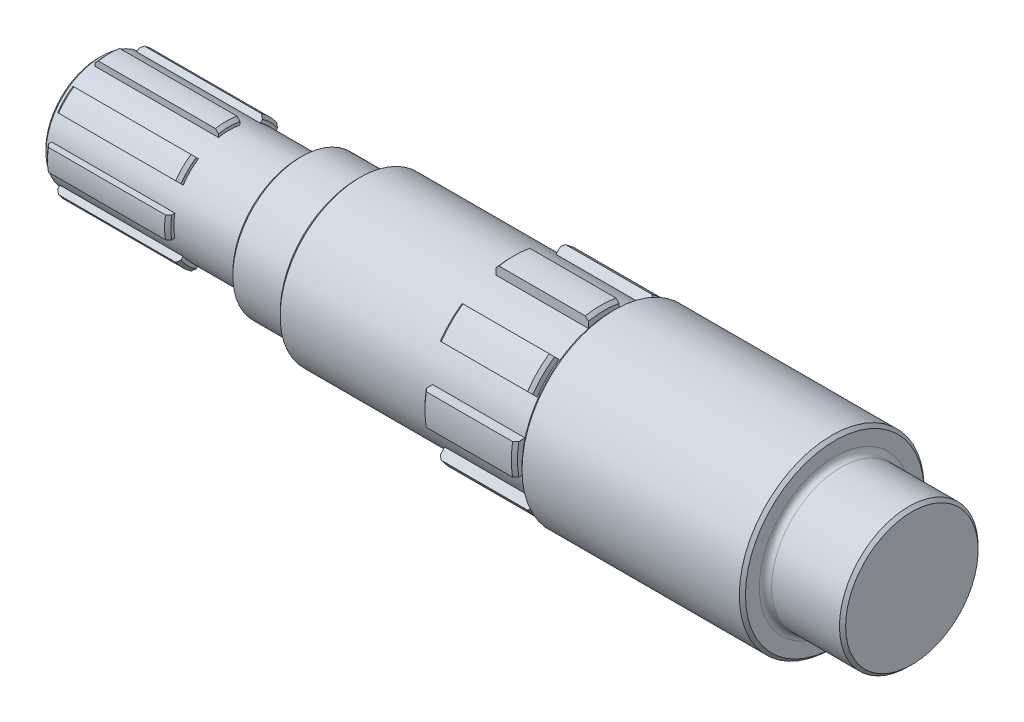
SolidWorks part; units mm, degrees
ref_plane "Front Plane" through (0, 0, 0) normal (0, 0, 1) x (1, 0, 0)
ref_plane "Top Plane" through (0, 0, 0) normal (0, 1, 0) x (1, 0, 0)
ref_plane "Right Plane" through (0, 0, 0) normal (1, 0, 0) x (0, 0, -1)
sketch "Sketch1" plane through (0, 0, 0) normal (0, 0, 1) x (1, 0, 0)
  line L0 (-155.9565, 0) -> (190.3478, 0) construction
  line L1 (-90.9565, 18) -> (-90.9565, 22.3478)
  line L2 (-90.9565, 22.3478) -> (-71.9565, 22.3478)
  line L3 (-71.9565, 22.3478) -> (-71.9565, 26)
  line L4 (-71.9565, 26) -> (-21.9565, 26)
  line L5 (10.5435, 26) -> (10.5435, 30)
  line L6 (10.5435, 30) -> (83.0435, 30)
  line L7 (83.0435, 30) -> (83.0435, 22.5)
  line L8 (83.0435, 22.5) -> (108.0435, 22.5)
  line L9 (108.0435, 22.5) -> (108.0435, 0)
  line L10 (-21.9565, 26) -> (-21.9565, 29)
  line L11 (-21.9565, 29) -> (8.0435, 29)
  line L12 (8.0435, 29) -> (8.0435, 26)
  line L13 (8.0435, 26) -> (10.5435, 26)
  line L14 (-90.9565, 18) -> (-113.4565, 18)
  line L15 (-155.9565, 18) -> (-155.9565, 0)
  line L16 (-155.9565, 0) -> (108.0435, 0)
  line L17 (-153.4565, 18) -> (-153.4565, 20)
  line L18 (-153.4565, 20) -> (-113.4565, 20)
  line L19 (-113.4565, 20) -> (-113.4565, 18)
  line L20 (-153.4565, 18) -> (-155.9565, 18)
  point P3 (-133.4565, 18)
  point P11 (-6.9565, 26)
  point P19 (-155.9565, 75.4675)
  dimension "D2" = 19
  dimension "D3" = 82.5
  dimension "D4" = 72.5
  dimension "D5" = 25
  dimension "D6" = 52
  dimension "D7" = 60
  dimension "D8" = 45
  dimension "D9" = 17.5
  dimension "D10" = 15
  dimension "D11" = 30
  dimension "D12" = 58
  dimension "D13" = 65
  dimension "D14" = 36
  dimension "D15" = 2.5
  dimension "D16" = 20
  dimension "D17" = 40
  dimension "D18" = 20
revolve "Revolve1" add sketch "Sketch1" angle 360 about L0
chamfer "Chamfer1" distance 1 angle 45 10 edges at (108.0435, 0, 22.5) (83.0435, 0, 30) (10.5435, 0, 30) (8.0435, 0, 29) (-21.9565, 0, 29) (-71.9565, 0, 26) (-90.9565, 0, 22.3478) (-113.4565, 0, 20) (-153.4565, 0, 20) (-155.9565, 0, 18)
sketch "Sketch2" plane through (-153.4565, 0, 0) normal (-1, 0, 0) x (0, 0, 1)
  line L0 (0, 0) -> (0, 34.2808) construction
  line L1 (-3.5, 19.6914) -> (-3.5, 17.6564)
  line L2 (3.5, 19.6914) -> (3.5, 17.6564)
  line L3 (16.3988, 11.449) -> (14.9599, 10.0101)
  line L4 (11.449, 16.3988) -> (10.0101, 14.9599)
  line L5 (19.6914, -3.5) -> (17.6564, -3.5)
  line L6 (19.6914, 3.5) -> (17.6564, 3.5)
  line L7 (11.449, -16.3988) -> (10.0101, -14.9599)
  line L8 (16.3988, -11.449) -> (14.9599, -10.0101)
  line L9 (-3.5, -19.6914) -> (-3.5, -17.6564)
  line L10 (3.5, -19.6914) -> (3.5, -17.6564)
  line L11 (-16.3988, -11.449) -> (-14.9599, -10.0101)
  line L12 (-11.449, -16.3988) -> (-10.0101, -14.9599)
  line L13 (-19.6914, 3.5) -> (-17.6564, 3.5)
  line L14 (-19.6914, -3.5) -> (-17.6564, -3.5)
  line L15 (-11.449, 16.3988) -> (-10.0101, 14.9599)
  line L16 (-16.3988, 11.449) -> (-14.9599, 10.0101)
  circle A0 centre (0, 0) radius 20 construction
  circle A1 centre (0, 0) radius 18 construction
  arc A2 (-3.5, 19.6914) -> (-11.449, 16.3988) centre (0, 0) ccw
  arc A3 (-3.5, 17.6564) -> (-10.0101, 14.9599) centre (0, 0) ccw
  arc A4 (11.449, 16.3988) -> (3.5, 19.6914) centre (0, 0) ccw
  arc A5 (10.0101, 14.9599) -> (3.5, 17.6564) centre (0, 0) ccw
  arc A6 (-16.3988, 11.449) -> (-19.6914, 3.5) centre (0, 0) ccw
  arc A7 (-14.9599, 10.0101) -> (-17.6564, 3.5) centre (0, 0) ccw
  arc A8 (-19.6914, -3.5) -> (-16.3988, -11.449) centre (0, 0) ccw
  arc A9 (-17.6564, -3.5) -> (-14.9599, -10.0101) centre (0, 0) ccw
  arc A10 (-11.449, -16.3988) -> (-3.5, -19.6914) centre (0, 0) ccw
  arc A11 (-10.0101, -14.9599) -> (-3.5, -17.6564) centre (0, 0) ccw
  arc A12 (3.5, -19.6914) -> (11.449, -16.3988) centre (0, 0) ccw
  arc A13 (3.5, -17.6564) -> (10.0101, -14.9599) centre (0, 0) ccw
  arc A14 (16.3988, -11.449) -> (19.6914, -3.5) centre (0, 0) ccw
  arc A15 (14.9599, -10.0101) -> (17.6564, -3.5) centre (0, 0) ccw
  arc A16 (19.6914, 3.5) -> (16.3988, 11.449) centre (0, 0) ccw
  arc A17 (17.6564, 3.5) -> (14.9599, 10.0101) centre (0, 0) ccw
  point P41 (0, 0)
  dimension "D1" = 3.5
  dimension "D2" = 8
extrude "Cut-Extrude1" cut sketch "Sketch2" against normal up to surface (40 mm away) up to face at (-113.4565, 0, 19)
sketch "Sketch3" plane through (-21.9565, 0, 0) normal (-1, 0, 0) x (0, 0, 1)
  line L0 (0, 0) -> (0, 40.4461) construction
  line L1 (-5, 28.5657) -> (-5, 25.5147)
  line L2 (5, 28.5657) -> (5, 25.5147)
  line L3 (16.6635, 23.7345) -> (14.5061, 21.5772)
  line L4 (23.7345, 16.6635) -> (21.5772, 14.5061)
  line L5 (28.5657, 5) -> (25.5147, 5)
  line L6 (28.5657, -5) -> (25.5147, -5)
  line L7 (23.7345, -16.6635) -> (21.5772, -14.5061)
  line L8 (16.6635, -23.7345) -> (14.5061, -21.5772)
  line L9 (5, -28.5657) -> (5, -25.5147)
  line L10 (-5, -28.5657) -> (-5, -25.5147)
  line L11 (-16.6635, -23.7345) -> (-14.5061, -21.5772)
  line L12 (-23.7345, -16.6635) -> (-21.5772, -14.5061)
  line L13 (-28.5657, -5) -> (-25.5147, -5)
  line L14 (-28.5657, 5) -> (-25.5147, 5)
  line L15 (-23.7345, 16.6635) -> (-21.5772, 14.5061)
  line L16 (-16.6635, 23.7345) -> (-14.5061, 21.5772)
  circle A0 centre (0, 0) radius 26 construction
  circle A1 centre (0, 0) radius 29 construction
  arc A2 (-5, 25.5147) -> (-14.5061, 21.5772) centre (0, 0) ccw
  arc A3 (-5, 28.5657) -> (-16.6635, 23.7345) centre (0, 0) ccw
  arc A4 (16.6635, 23.7345) -> (5, 28.5657) centre (0, 0) ccw
  arc A5 (14.5061, 21.5772) -> (5, 25.5147) centre (0, 0) ccw
  arc A6 (28.5657, 5) -> (23.7345, 16.6635) centre (0, 0) ccw
  arc A7 (25.5147, 5) -> (21.5772, 14.5061) centre (0, 0) ccw
  arc A8 (23.7345, -16.6635) -> (28.5657, -5) centre (0, 0) ccw
  arc A9 (21.5772, -14.5061) -> (25.5147, -5) centre (0, 0) ccw
  arc A10 (5, -28.5657) -> (16.6635, -23.7345) centre (0, 0) ccw
  arc A11 (5, -25.5147) -> (14.5061, -21.5772) centre (0, 0) ccw
  arc A12 (-16.6635, -23.7345) -> (-5, -28.5657) centre (0, 0) ccw
  arc A13 (-14.5061, -21.5772) -> (-5, -25.5147) centre (0, 0) ccw
  arc A14 (-28.5657, -5) -> (-23.7345, -16.6635) centre (0, 0) ccw
  arc A15 (-25.5147, -5) -> (-21.5772, -14.5061) centre (0, 0) ccw
  arc A16 (-23.7345, 16.6635) -> (-28.5657, 5) centre (0, 0) ccw
  arc A17 (-21.5772, 14.5061) -> (-25.5147, 5) centre (0, 0) ccw
  point P41 (0, 0)
  dimension "D1" = 5
  dimension "D2" = 8
extrude "Cut-Extrude2" cut sketch "Sketch3" against normal up to surface (30 mm away) up to face at (8.0435, 0, 28)
fillet "Fillet1" radius 2 4 edges at (83.0435, 0, 22.5) (10.5435, 0, 26) (-71.9565, 0, 22.3478) (-90.9565, 0, 18)
